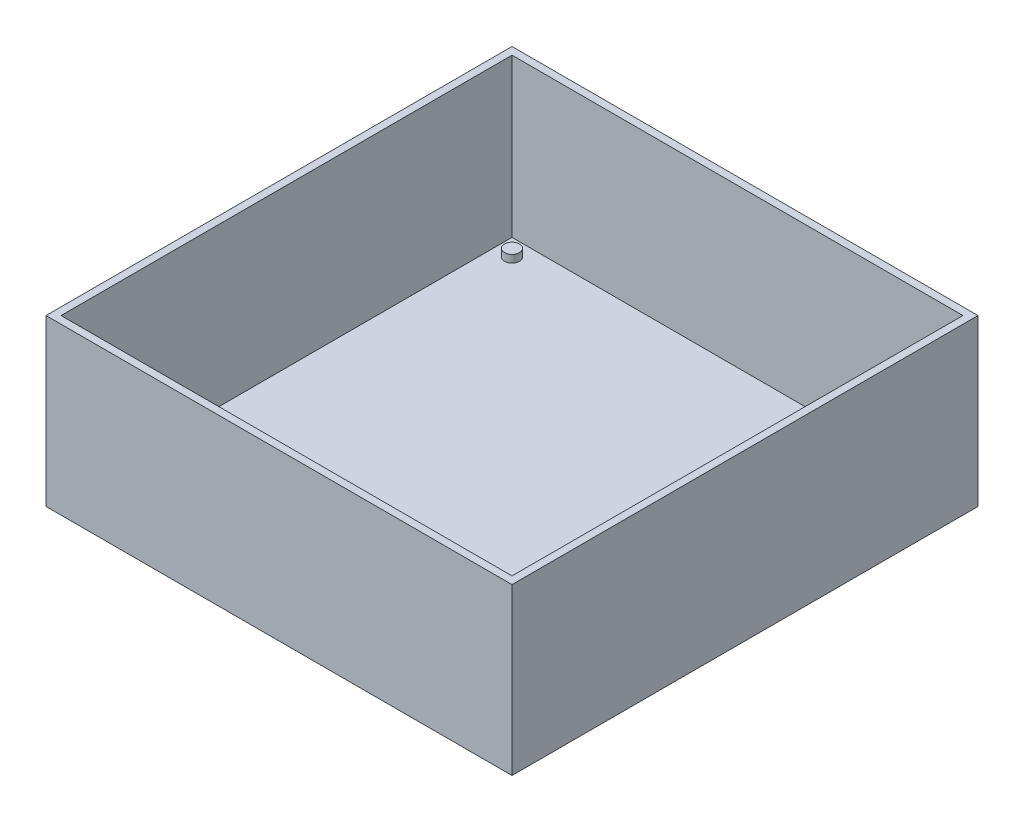
SolidWorks part; units mm, degrees
ref_plane "前视基准面" through (0, 0, 0) normal (0, 0, 1) x (1, 0, 0)
ref_plane "上视基准面" through (0, 0, 0) normal (0, 1, 0) x (1, 0, 0)
ref_plane "右视基准面" through (0, 0, 0) normal (1, 0, 0) x (0, 0, -1)
sketch "草图2" plane through (0, 0, 0) normal (0, 1, 0) x (1, 0, 0)
  line L1 (0, 0) -> (124, 0)
  line L2 (0, 0) -> (0, 124)
  line L3 (0, 124) -> (124, 124)
  line L4 (124, 0) -> (124, 124)
extrude "凸台-拉伸1" add sketch "草图2" along normal blind 2
sketch "草图6" plane through (0, 2, 0) normal (0, 1, 0) x (1, 0, 0)
  line L1 (0, 0) -> (124, 0)
  line L2 (0, 0) -> (0, 124)
  line L3 (0, 124) -> (124, 124)
  line L4 (124, 0) -> (124, 124)
  line L5 (2, 2) -> (122, 2)
  line L6 (2, 2) -> (2, 122)
  line L7 (2, 122) -> (122, 122)
  line L8 (122, 2) -> (122, 122)
extrude "凸台-拉伸3" add sketch "草图6" along normal blind 42
sketch "草图7" plane through (0, 2, 0) normal (0, 1, 0) x (1, 0, 0)
  circle A0 centre (6.5, 6.5) radius 2
  circle A1 centre (117.5, 6.5) radius 2
  circle A2 centre (6.5, 117.5) radius 2
  circle A3 centre (117.5, 117.5) radius 2
extrude "凸台-拉伸4" add sketch "草图7" along normal blind 2
